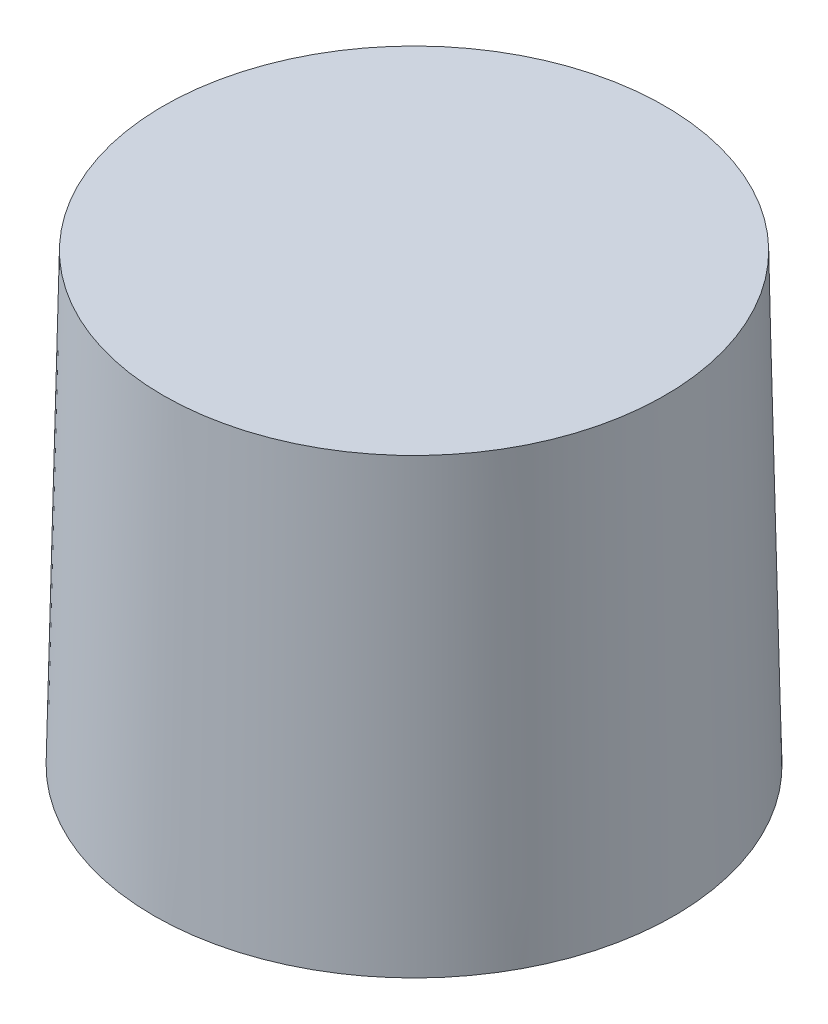
SolidWorks part; units mm, degrees
material "ABS PC"
ref_plane "Plano frontal" through (0, 0, 0) normal (0, 0, 1) x (1, 0, 0)
ref_plane "Plano superior" through (0, 0, 0) normal (0, 1, 0) x (1, 0, 0)
ref_plane "Plano direito" through (0, 0, 0) normal (1, 0, 0) x (0, 0, -1)
sketch "Esboço1" plane through (0, 0, 0) normal (0, 0, 1) x (1, 0, 0)
  line L0 (0, 57.8356) -> (0, -115.305) construction
  line L1 (0, 0) -> (-27, 0)
  line L2 (-27, 0) -> (-30, -142) construction
  line L3 (-30, -142) -> (-27.9996, -142) construction
  line L4 (-27.9996, -142) -> (-25.0418, -2.0004) construction
  line L5 (-25.0418, -2.0004) -> (0, -2.0004)
  line L6 (0, -2.0004) -> (0, 0)
  line L7 (-25.0418, -2.0004) -> (-26.0136, -48)
  line L8 (-26.0136, -48) -> (-28.0141, -48)
  line L9 (-28.0141, -48) -> (-27, 0)
  dimension "D2" = 30
  dimension "D3" = 2
  dimension "D1" = 27
  dimension "D4" = 142
  dimension "D5" = 48
revolve "Revolução1" add sketch "Esboço1" angle 360 about L0
